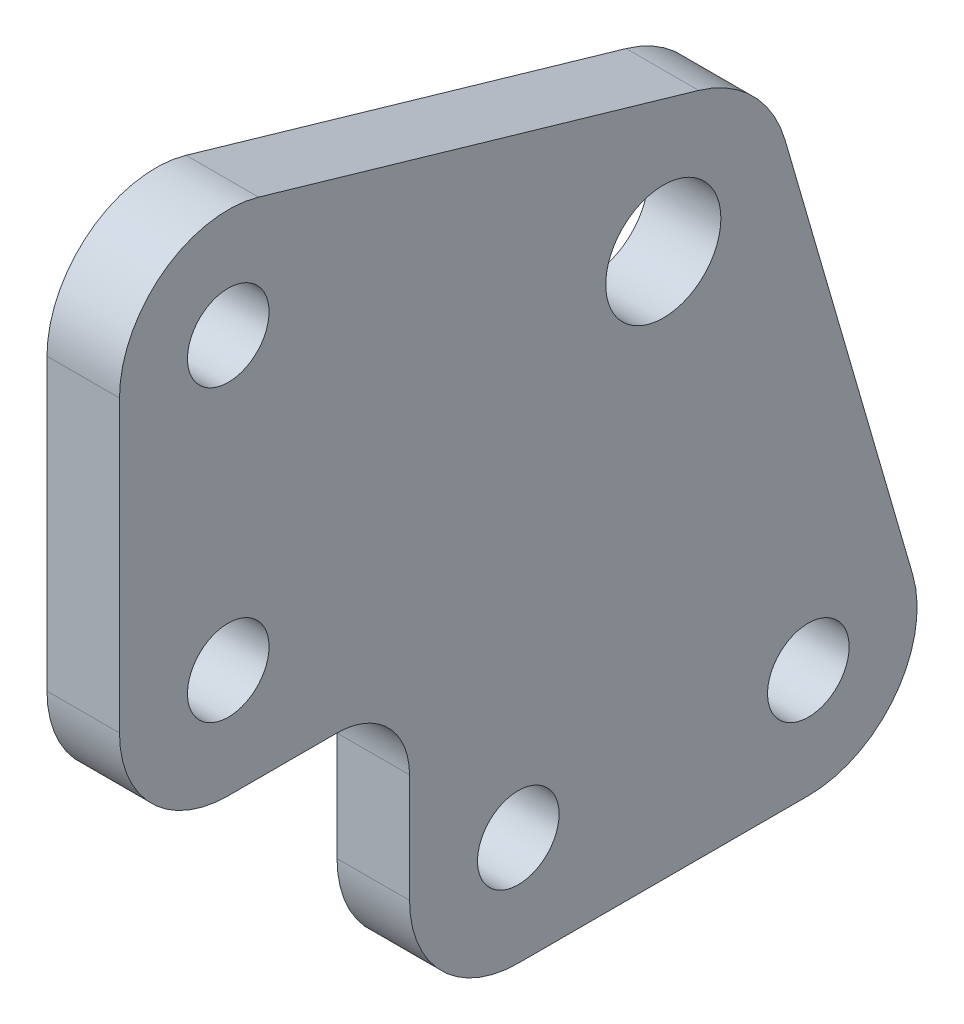
SolidWorks part; units mm, degrees
ref_plane "Front Plane" through (0, 0, 0) normal (0, 0, 1) x (1, 0, 0)
ref_plane "Top Plane" through (0, 0, 0) normal (0, 1, 0) x (1, 0, 0)
ref_plane "Right Plane" through (0, 0, 0) normal (1, 0, 0) x (0, 0, -1)
sketch "Sketch1" plane through (0, 0, 0) normal (1, 0, 0) x (0, 0, -1)
  line L0 (-1338.0003, 195.7046) -> (-1338.0003, 170.3046) construction
  line L1 (-1328.4753, 160.7796) -> (-1312.6003, 160.7796) construction
  line L2 (-1312.6003, 160.7796) -> (-1312.6003, 144.9046) construction
  line L3 (-1303.0753, 135.3796) -> (-1277.6753, 135.3796) construction
  line L4 (-1279.7024, 186.0992) -> (-1268.5271, 147.5571) construction
  line L5 (-1338.0003, 195.7046) -> (-1338.0003, 170.3046)
  line L6 (-1328.4753, 160.7796) -> (-1312.6003, 160.7796)
  line L7 (-1312.6003, 160.7796) -> (-1312.6003, 144.9046)
  line L8 (-1303.0753, 135.3796) -> (-1277.6753, 135.3796)
  line L9 (-1279.7024, 186.0992) -> (-1268.5271, 147.5571)
  line L10 (-1325.8228, 204.8528) -> (-1287.2807, 193.6775) construction
  line L11 (-1325.8228, 204.8528) -> (-1287.2807, 193.6775)
  circle A0 centre (-1328.4753, 170.3046) radius 9.525 construction
  circle A1 centre (-1303.0753, 144.9046) radius 9.525 construction
  circle A2 centre (-1277.6753, 144.9046) radius 9.525 construction
  arc A3 (-1338.0003, 170.3046) -> (-1328.4753, 160.7796) centre (-1328.4753, 170.3046) ccw
  arc A4 (-1312.6003, 144.9046) -> (-1303.0753, 135.3796) centre (-1303.0753, 144.9046) ccw
  arc A5 (-1277.6753, 135.3796) -> (-1268.5271, 147.5571) centre (-1277.6753, 144.9046) ccw
  circle A6 centre (-1328.4753, 195.7046) radius 9.525 construction
  arc A7 (-1325.8228, 204.8528) -> (-1338.0003, 195.7046) centre (-1328.4753, 195.7046) ccw
  circle A8 centre (-1290.3753, 183.0046) radius 11.1125 construction
  arc A9 (-1279.7024, 186.0992) -> (-1287.2807, 193.6775) centre (-1290.3753, 183.0046) ccw
extrude "Boss-Extrude1" add sketch "Sketch1" along normal up to vertex (18.7389 mm away) from vertex at 12.3889
hole_wizard "3/8 Clearance Hole1" positions "Sketch2" profile "Sketch3" hole size "3/8" standard "ANSI Inch" end condition through all
sketch "Sketch2" plane through (18.7389, 0, 0) normal (1, 0, 0) x (0, 0, -1)
  point P0 (-1290.3753, 183.0046)
sketch "Sketch3" plane through (18.7389, 183.0046, 1290.3753) normal (0, 1, 0) x (0, 0, -1)
  line L0 (0, 0) -> (0, 6.35)
  line L1 (0, 6.35) -> (5.0419, 6.35)
  line L2 (5.0419, 6.35) -> (5.0419, 0)
  line L5 (5.0419, 0) -> (0, 0)
  line L11 (0, -6.35) -> (0, 107.95) construction
  dimension "Thru Hole Dia." = 10.0838
  dimension "Thru Hole Depth" = 6.35
hole_wizard "1/4 Clearance Hole1" positions "Sketch4" profile "Sketch5" hole size "1/4" standard "ANSI Inch" end condition through all
sketch "Sketch4" plane through (18.7389, 0, 0) normal (1, 0, 0) x (0, 0, -1)
  point P0 (-1303.0753, 144.9046)
  point P3 (-1277.6753, 144.9046)
  point P6 (-1328.4753, 170.3046)
  point P9 (-1328.4753, 195.7046)
sketch "Sketch5" plane through (18.7389, 144.9046, 1303.0753) normal (0, 1, 0) x (0, 0, -1)
  line L0 (0, 0) -> (0, 6.35)
  line L1 (0, 6.35) -> (3.5712, 6.35)
  line L2 (3.5712, 6.35) -> (3.5712, 0)
  line L5 (3.5712, 0) -> (0, 0)
  line L11 (0, -6.35) -> (0, 107.95) construction
  dimension "Thru Hole Dia." = 7.1425
  dimension "Thru Hole Depth" = 6.35
fillet "Fillet1" radius 6.35 1 edges at (15.5639, 160.7796, 1312.6003)
